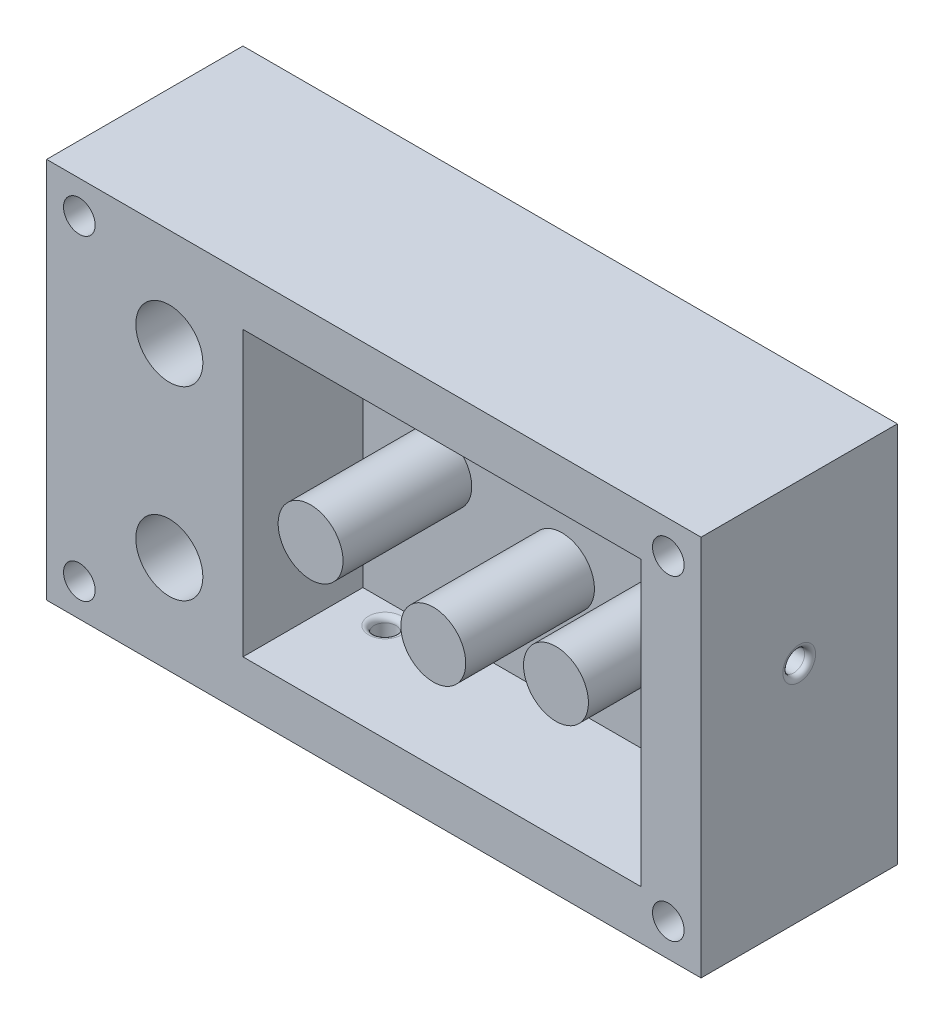
SolidWorks part; units mm, degrees
ref_plane "Front Plane" through (0, 0, 0) normal (0, 0, 1) x (1, 0, 0)
ref_plane "Top Plane" through (0, 0, 0) normal (0, 1, 0) x (1, 0, 0)
ref_plane "Right Plane" through (0, 0, 0) normal (1, 0, 0) x (0, 0, -1)
sketch "Sketch1" plane through (0, 0, 0) normal (0, 0, 1) x (1, 0, 0)
  line L1 (0, 0) -> (60, 0)
  line L2 (0, 0) -> (0, 35)
  line L3 (0, 35) -> (60, 35)
  line L4 (60, 0) -> (60, 35)
  dimension "D1" = 60
  dimension "D2" = 35
extrude "Boss-Extrude1" add sketch "Sketch1" along normal blind 18 contours L2 L1 L4 L3
sketch "Sketch2" plane through (0, 0, 18) normal (0, 0, 1) x (1, 0, 0)
  line L0 (0, 32.5) -> (60, 32.5) construction
  line L1 (0, 0) -> (0, 35) construction
  line L2 (60, 0) -> (60, 35) construction
  line L3 (0, 2.5) -> (60, 2.5) construction
  line L4 (2.5, 35) -> (2.5, 0) construction
  line L5 (0, 35) -> (60, 35) construction
  line L6 (0, 0) -> (60, 0) construction
  line L7 (57.5, 35) -> (57.5, 0) construction
  line L8 (20, 35) -> (20, 0) construction
  line L9 (11.25, 35) -> (11.25, 0) construction
  circle A0 centre (11.25, 26) radius 3.075
  circle A1 centre (11.25, 9) radius 3.075
  dimension "D7" = 6.15
  dimension "D8" = 17
  dimension "D1" = 2.5
  dimension "D2" = 2.5
  dimension "D3" = 2.5
  dimension "D4" = 2.5
  dimension "D5" = 20
  dimension "D6" = 8.75
  dimension "D9" = 9
extrude "Cut-Extrude1" cut sketch "Sketch2" against normal blind 18
sketch "Sketch3" plane through (0, 0, 18) normal (0, 0, 1) x (1, 0, 0)
  line L0 (0, 32) -> (60, 32) construction
  line L1 (0, 0) -> (0, 35) construction
  line L2 (60, 0) -> (60, 35) construction
  line L3 (3, 35) -> (3, 0) construction
  line L4 (0, 35) -> (60, 35) construction
  line L5 (0, 0) -> (60, 0) construction
  line L6 (0, 3) -> (60, 3) construction
  line L7 (57, 35) -> (57, 0) construction
  line L8 (18, 35) -> (18, 0) construction
  line L10 (18, 4.5) -> (54.5, 4.5)
  line L11 (18, 4.5) -> (18, 30.5)
  line L12 (18, 30.5) -> (54.5, 30.5)
  line L13 (54.5, 4.5) -> (54.5, 30.5)
  circle A0 centre (3, 32) radius 1.45
  circle A1 centre (57, 32) radius 1.45
  circle A2 centre (57, 3) radius 1.45
  circle A3 centre (3, 3) radius 1.45
  dimension "D6" = 2.9
  dimension "D1" = 3
  dimension "D2" = 3
  dimension "D3" = 3
  dimension "D4" = 3
  dimension "D5" = 18
  dimension "D7" = 1.5
  dimension "D8" = 1.5
  dimension "D9" = 2.5
extrude "Cut-Extrude2" cut sketch "Sketch3" against normal blind 11
sketch "Sketch4" plane through (0, 0, 7) normal (0, 0, 1) x (1, 0, 0)
  line L0 (18, 17.5) -> (54.5, 17.5) construction
  line L1 (18, 30.5) -> (18, 4.5) construction
  line L2 (54.5, 4.5) -> (54.5, 30.5) construction
  line L3 (18, 15) -> (54.5, 15) construction
  line L4 (54.5, 4.5) -> (54.5, 30.5) construction
  line L5 (18, 30.5) -> (18, 4.5) construction
  circle A0 centre (25, 17.5) radius 2.975
  circle A1 centre (36.25, 15) radius 2.975
  circle A2 centre (47.5, 17.5) radius 2.975
  dimension "D2" = 5.95
  dimension "D3" = 7
  dimension "D1" = 2.5
  dimension "D4" = 7
extrude "Boss-Extrude2" add sketch "Sketch4" along normal blind 11.8
sketch "Sketch6" plane through (60, 0, 0) normal (1, 0, 0) x (0, 0, -1)
  line L0 (-9, 35) -> (-9, 0) construction
  line L1 (-18, 35) -> (0, 35) construction
  line L2 (-18, 0) -> (0, 0) construction
  line L3 (-18, 20.475) -> (0, 20.475) construction
  line L4 (-18, 0) -> (-18, 35) construction
  line L5 (0, 0) -> (0, 35) construction
  circle A0 centre (-9, 20.475) radius 1
  dimension "D1" = 20.475
extrude "Cut-Extrude3" cut sketch "Sketch6" against normal blind 5.8
sketch "Sketch8" plane through (0, 0, 0) normal (0, -1, 0) x (1, 0, 0)
  line L0 (0, 9) -> (60, 9) construction
  line L1 (0, 18) -> (0, 0) construction
  line L2 (60, 18) -> (60, 0) construction
  line L3 (22.025, 18) -> (22.025, 0) construction
  line L4 (0, 18) -> (60, 18) construction
  line L5 (0, 0) -> (60, 0) construction
  circle A0 centre (22.025, 9) radius 1
  dimension "D1" = 37.975
extrude "Cut-Extrude4" cut sketch "Sketch8" against normal blind 5.8
fillet "Fillet2" radius 0.5 4 edges at (60, 20.475, 8) (54.5, 20.475, 8) (22.025, 4.5, 8) (22.025, 0, 8)
